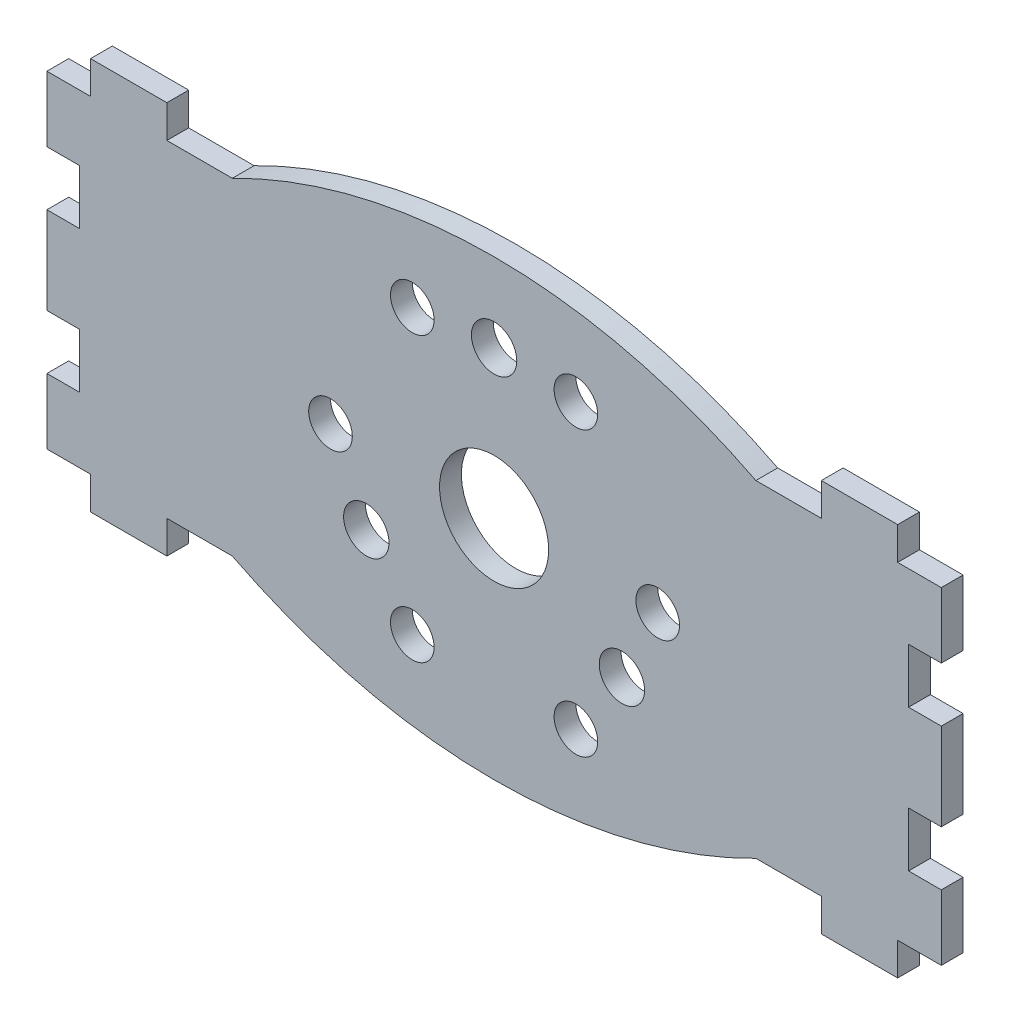
SolidWorks part; units mm, degrees
ref_plane "前视基准面" through (0, 0, 0) normal (0, 0, 1) x (1, 0, 0)
ref_plane "上视基准面" through (0, 0, 0) normal (0, 1, 0) x (1, 0, 0)
ref_plane "右视基准面" through (0, 0, 0) normal (1, 0, 0) x (0, 0, -1)
sketch "草图1" plane through (0, 0, 0) normal (0, 0, 1) x (1, 0, 0)
  line L269 (24, -15) -> (30, -15)
  line L275 (37, -18) -> (30, -18)
  line L286 (30, -15) -> (30, -18)
  line L287 (37, -18) -> (37, -15)
  line L288 (37, -15) -> (41, -15)
  line L362 (41, -11.75) -> (41, -15)
  line L389 (0, -15) -> (61.2365, -15) construction
  line L391 (41, 11.75) -> (41, 15)
  line L395 (37, 15) -> (41, 15)
  line L396 (37, 18) -> (37, 15)
  line L397 (30, 15) -> (30, 18)
  line L398 (37, 18) -> (30, 18)
  line L399 (24, 15) -> (30, 15)
  line L402 (-24, 15) -> (-30, 15)
  line L403 (-37, 18) -> (-30, 18)
  line L404 (-30, 15) -> (-30, 18)
  line L405 (-37, 18) -> (-37, 15)
  line L406 (-37, 15) -> (-41, 15)
  line L410 (-41, 11.75) -> (-41, 15)
  line L411 (-41, -11.75) -> (-41, -15)
  line L415 (-37, -15) -> (-41, -15)
  line L416 (-37, -18) -> (-37, -15)
  line L417 (-30, -15) -> (-30, -18)
  line L418 (-37, -18) -> (-30, -18)
  line L419 (-24, -15) -> (-30, -15)
  line L422 (-15, 0) -> (-61.4251, 0) construction
  line L423 (-41, 0) -> (-41, 4)
  line L424 (-41, 4) -> (-41, 0)
  line L425 (-41, 0) -> (-41, -4)
  line L426 (-41, -4) -> (-38, -4)
  line L427 (-38, -4) -> (-38, -9)
  line L428 (-38, -9) -> (-41, -9)
  line L429 (-41, -9) -> (-41, -11.75)
  line L430 (-41, 4) -> (-38, 4)
  line L431 (-38, 4) -> (-38, 9)
  line L432 (-38, 9) -> (-41, 9)
  line L433 (-41, 9) -> (-41, 11.75)
  line L434 (41, 9) -> (41, 11.75)
  line L435 (38, 9) -> (41, 9)
  line L436 (38, 4) -> (38, 9)
  line L437 (41, 4) -> (38, 4)
  line L438 (41, -9) -> (41, -11.75)
  line L439 (38, -9) -> (41, -9)
  line L440 (38, -4) -> (38, -9)
  line L441 (41, -4) -> (38, -4)
  line L442 (41, 0) -> (41, -4)
  line L443 (41, 4) -> (41, 0)
  line L444 (41, 0) -> (41, 4)
  circle A13 centre (0, 0) radius 15 construction
  circle A14 centre (0, 0) radius 13.53 construction
  circle A15 centre (-15, 0) radius 2
  circle A16 centre (-7.5, 12.9904) radius 2
  circle A17 centre (7.5, 12.9904) radius 2
  circle A18 centre (15, 0) radius 2
  circle A19 centre (7.5, -12.9904) radius 2
  circle A20 centre (-7.5, -12.9904) radius 2
  circle A21 centre (0, 13.53) radius 2.08
  circle A22 centre (11.7173, -6.765) radius 2.08
  circle A23 centre (-11.7173, -6.765) radius 2.08
  circle A24 centre (0, 0) radius 5
  arc A27 (-24, 15) -> (24, 15) centre (0, -32.0369) cw
  arc A28 (-24, -15) -> (24, -15) centre (0, 32.0369) ccw
  dimension "D1" = 6
extrude "凸台-拉伸2" add sketch "草图1" along normal blind 2
sketch "草图2" plane through (0, 0, 2) normal (0, 0, 1) x (1, 0, 0)
  line L0 (0, 0) -> (-23.47, 0) construction
  line L1 (0, 0) -> (0, 31.1485) construction
